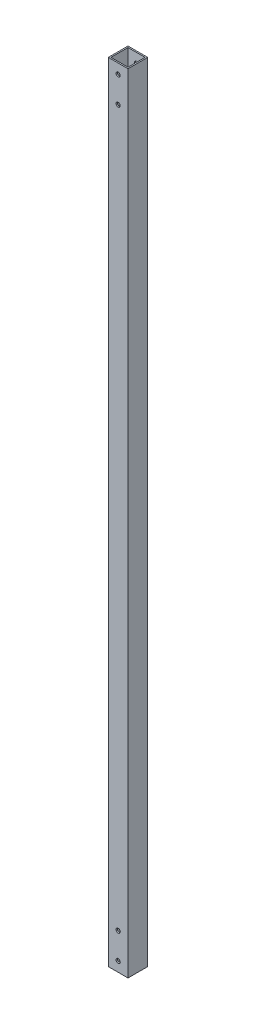
SolidWorks part; units mm, degrees
ref_plane "前视基准面" through (0, 0, 0) normal (0, 0, 1) x (1, 0, 0)
ref_plane "上视基准面" through (0, 0, 0) normal (0, 1, 0) x (1, 0, 0)
ref_plane "右视基准面" through (0, 0, 0) normal (1, 0, 0) x (0, 0, -1)
sketch "草图1" plane through (0, 0, 0) normal (0, 1, 0) x (1, 0, 0)
  line L1 (-7.5, -7.5) -> (7.5, -7.5)
  line L2 (-7.5, -7.5) -> (-7.5, 7.5)
  line L3 (-7.5, 7.5) -> (7.5, 7.5)
  line L4 (7.5, -7.5) -> (7.5, 7.5)
  line L5 (-7.5, -7.5) -> (7.5, 7.5) construction
  line L6 (-7.5, 7.5) -> (7.5, -7.5) construction
  point P0 (0, 0)
  dimension "D1" = 15
  dimension "D2" = 15
extrude "拉伸-薄壁1" add sketch "草图1" along normal blind 600 thin thin type one direction reverse wall 1
sketch "草图2" plane through (0, 0, 7.5) normal (0, 0, 1) x (1, 0, 0)
  line L0 (0, 0) -> (0, 600) construction
  line L1 (-7.5, 600) -> (7.5, 600) construction
  line L2 (-7.5, 0) -> (7.5, 0) construction
  circle A0 centre (0, 7.5) radius 1.6
  circle A1 centre (0, 27.5) radius 1.6
  circle A2 centre (0, 592.5) radius 1.6
  circle A3 centre (0, 572.5) radius 1.6
  dimension "D1" = 3.2
  dimension "D2" = 7.5
  dimension "D3" = 20
  dimension "D5" = 20
  dimension "D4" = 565
extrude "切除-拉伸1" cut sketch "草图2" against normal through all
